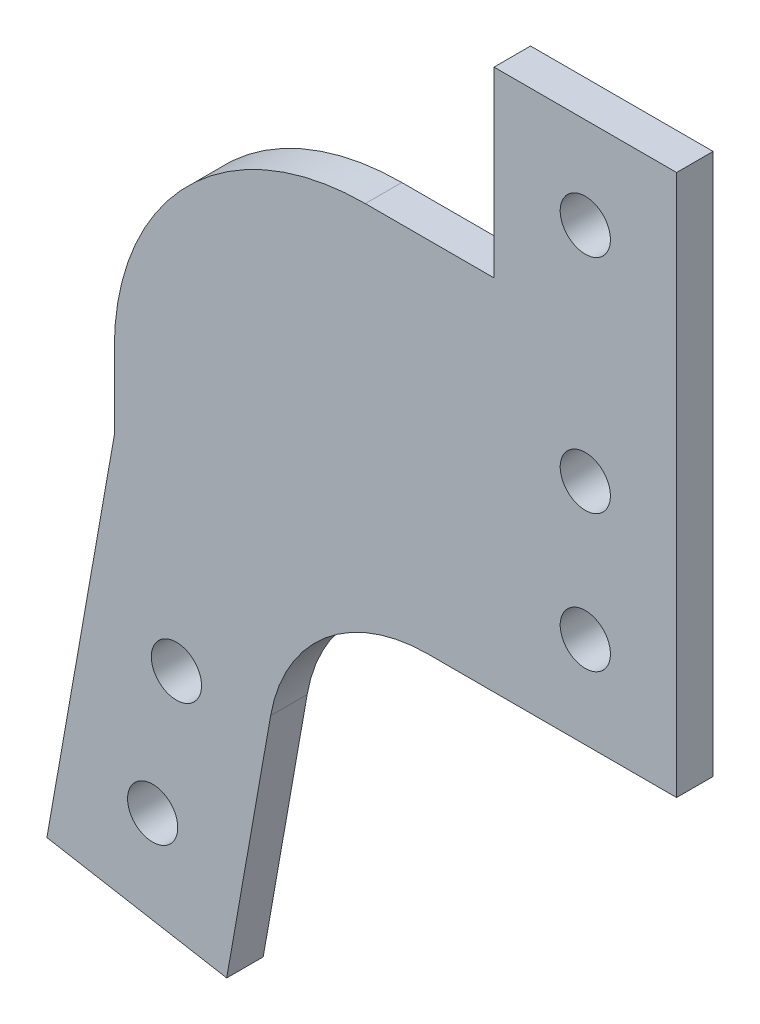
SolidWorks part; units mm, degrees
ref_plane "Front Plane" through (0, 0, 0) normal (0, 0, 1) x (1, 0, 0)
ref_plane "Top Plane" through (0, 0, 0) normal (0, 1, 0) x (1, 0, 0)
ref_plane "Right Plane" through (0, 0, 0) normal (1, 0, 0) x (0, 0, -1)
sketch "Sketch1" plane through (0, 0, 0) normal (0, 0, 1) x (1, 0, 0)
  line L0 (14.6842, 0) -> (41.9206, 0)
  line L1 (41.9206, 0) -> (41.9206, 59.3)
  line L2 (41.9206, 59.3) -> (21.9206, 59.3)
  line L3 (21.9206, 59.3) -> (21.9206, 39.3)
  line L4 (21.9206, 39.3) -> (7.8206, 39.3)
  line L5 (-27.0595, -38.2864) -> (-19.6794, 3.5679)
  line L6 (-19.6794, 3.5679) -> (-19.6794, 11.8)
  line L7 (-27.0595, -38.2864) -> (-7.3633, -41.7594)
  line L8 (-7.3633, -41.7594) -> (-2.5499, -14.4612)
  line L9 (-7.3633, -41.7594) -> (75.268, -41.7594) construction
  circle A0 centre (31.9206, 49.3) radius 2.75
  circle A1 centre (31.9206, 25) radius 2.75
  circle A2 centre (31.9206, 10) radius 2.75
  circle A3 centre (-15.4749, -30.1749) radius 2.75
  circle A4 centre (-12.8702, -15.4027) radius 2.75
  arc A5 (7.8206, 39.3) -> (-19.6794, 11.8) centre (7.8206, 11.8) ccw
  arc A6 (-2.5499, -14.4612) -> (14.6842, 0) centre (14.6842, -17.5) cw
  point P27 (-19.6794, 39.3)
  point P30 (0, 0)
  dimension "D9" = 5.5
  dimension "D10" = 10
  dimension "D11" = 10
  dimension "D14" = 10
  dimension "D15" = 10
  dimension "D18" = 27.5
  dimension "D19" = 17.5
  dimension "D1" = 59.3
  dimension "D2" = 20
  dimension "D3" = 20
  dimension "D4" = 20
  dimension "D5" = 41.6
  dimension "D6" = 80
  dimension "D7" = 35.7321
  dimension "D8" = 42.5
  dimension "D12" = 15
  dimension "D13" = 10
  dimension "D16" = 15
  dimension "D17" = 10
extrude "Boss-Extrude1" add sketch "Sketch1" along normal blind 4
